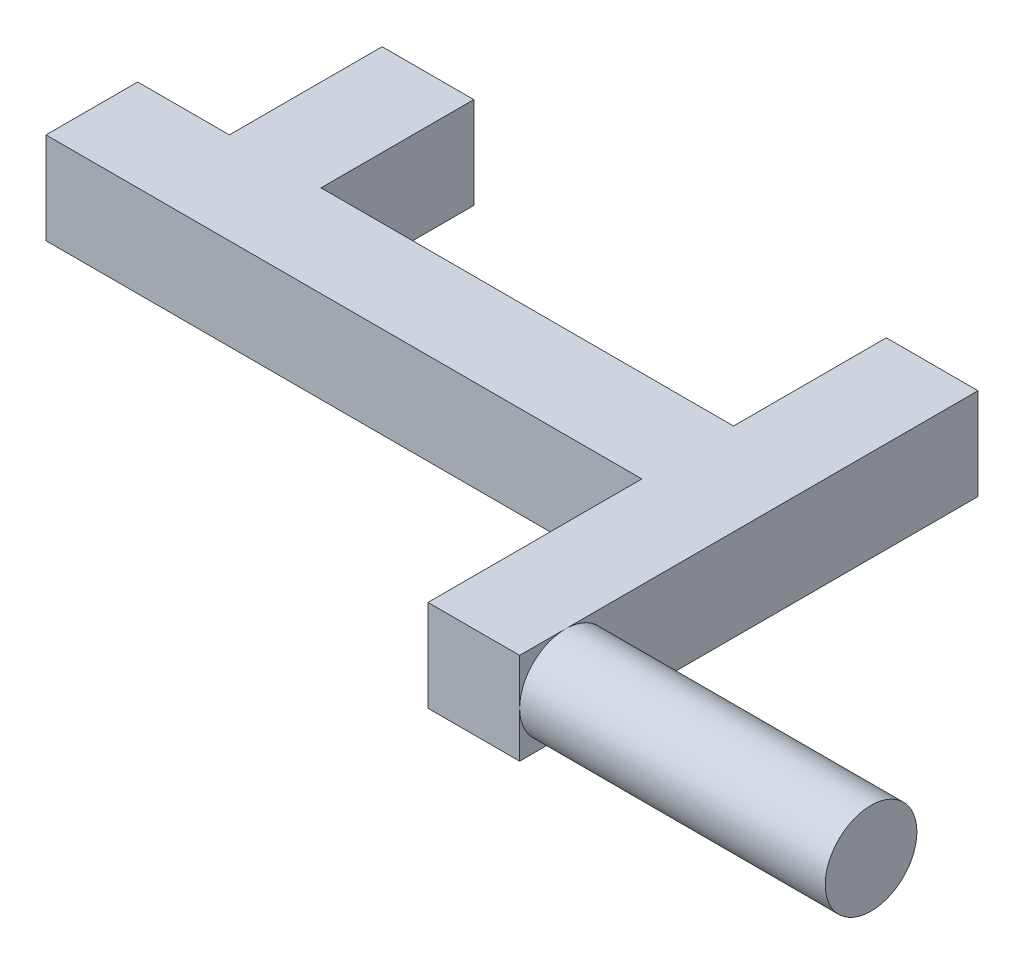
SolidWorks part; units mm, degrees
ref_plane "Plano frontal" through (0, 0, 0) normal (0, 0, 1) x (1, 0, 0)
ref_plane "Plano superior" through (0, 0, 0) normal (0, 1, 0) x (1, 0, 0)
ref_plane "Plano direito" through (0, 0, 0) normal (1, 0, 0) x (0, 0, -1)
sketch "Esboço1" plane through (0, 0, 0) normal (0, 1, 0) x (1, 0, 0)
  line L0 (0, 0) -> (6, 0)
  line L1 (6, 0) -> (6, -10)
  line L2 (6, -10) -> (12, -10)
  line L3 (45, -10) -> (45, 0)
  line L4 (45, 0) -> (51, 0)
  line L5 (51, 0) -> (51, -24)
  line L6 (51, -24) -> (71, -24)
  line L7 (71, -24) -> (71, -30)
  line L8 (71, -30) -> (45, -30)
  line L9 (45, -30) -> (45, -16)
  line L10 (45, -16) -> (0, -16)
  line L11 (0, -16) -> (0, 0)
  line L12 (12, -10) -> (12, 0)
  line L13 (12, 0) -> (18, 0)
  line L14 (18, 0) -> (18, -10)
  line L15 (18, -10) -> (45, -10)
  line L16 (6, 0) -> (6, -16)
  line L17 (6, -16) -> (0, -16)
  line L18 (0, 0) -> (6, 0)
  dimension "D1" = 6
  dimension "D2" = 45
  dimension "D3" = 6
  dimension "D4" = 20
  dimension "D5" = 30
  dimension "D6" = 6
  dimension "D7" = 10
  dimension "D8" = 6
  dimension "D9" = 6
extrude "Ressalto-extrusão3" add sketch "Esboço1" along normal blind 6 contours L2 L16 L10 L9 L8 L7 L6 L5 L4 L3 L15 L14 L13 L12
ref_plane "Plano1" through (71, 0, 0) normal (1, 0, 0) x (0, 0, -1)
sketch "Esboço2" plane through (71, 0, 0) normal (1, 0, 0) x (0, 0, -1)
  line L0 (-30, 6) -> (-30, 0) construction
  line L1 (-24, 0) -> (-30, 0) construction
  line L2 (-24, 6) -> (-24, 0) construction
  line L3 (-30, 3) -> (-30, 6)
  line L4 (-30, 6) -> (-27, 6)
  line L5 (-27, 6) -> (-24, 6)
  line L6 (-24, 6) -> (-24, 3)
  line L7 (-24, 3) -> (-24, 0)
  line L8 (-24, 0) -> (-27, 0)
  line L9 (-27, 0) -> (-30, 0)
  line L10 (-30, 0) -> (-30, 3)
  circle A0 centre (-27, 3) radius 3
extrude "Corte-extrusão1" cut sketch "Esboço2" against normal blind 20 contours A0 L4 L3 | A0 L6 L5 | A0 L8 L7 | A0 L10 L9
